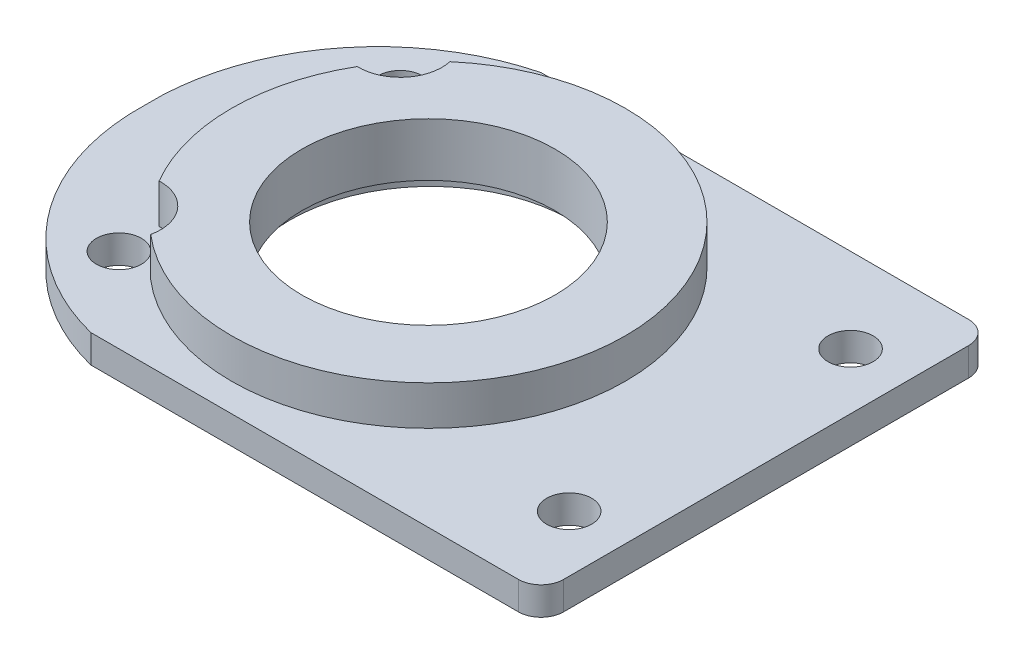
SolidWorks part; units mm, degrees
ref_plane "Front Plane" through (0, 0, 0) normal (0, 0, 1) x (1, 0, 0)
ref_plane "Top Plane" through (0, 0, 0) normal (0, 1, 0) x (1, 0, 0)
ref_plane "Right Plane" through (0, 0, 0) normal (1, 0, 0) x (0, 0, -1)
sketch "Sketch1" plane through (0, 0, 0) normal (0, 1, 0) x (1, 0, 0)
  line L1 (0, 0) -> (76.2, 0)
  line L2 (0, 0) -> (0, 50.8)
  line L3 (0, 50.8) -> (76.2, 50.8)
  line L4 (76.2, 0) -> (76.2, 50.8)
  circle A0 centre (38.1, 25.4) radius 14.2748
  dimension "D5" = 28.5496
  dimension "D1" = 50.8
  dimension "D2" = 76.2
  dimension "D3" = 38.1
  dimension "D4" = 25.4
extrude "Boss-Extrude1" add sketch "Sketch1" along normal blind 3.175
sketch "Sketch2" plane through (0, 3.175, 0) normal (0, 1, 0) x (1, 0, 0)
  circle A0 centre (38.1, 25.4) radius 22.225
  dimension "D1" = 44.45
extrude "Boss-Extrude2" add sketch "Sketch2" along normal blind 4.445
sketch "Sketch3" plane through (0, 3.175, 0) normal (0, -1, 0) x (1, 0, 0)
  circle A1 centre (38.1, -25.4) radius 14.2748
  circle A2 centre (38.1, -25.4) radius 14.2748
  dimension "D1" = 0
extrude "Cut-Extrude1" cut sketch "Sketch3" against normal through all
sketch "Sketch4" plane through (0, 0, 0) normal (0, -1, 0) x (-1, 0, 0)
  line L0 (0, 0) -> (-76.2, 0) construction
  circle A0 centre (-38.3325, 25.4) radius 15.8623
  dimension "D1" = 31.7246
  dimension "D2" = 25.4
extrude "Cut-Extrude2" cut sketch "Sketch4" against normal blind 1.6002
fillet "Fillet2" radius 2.54 4 edges at (0, 1.5875, -50.8) (76.2, 1.5875, -50.8) (0, 1.5875, 0) (76.2, 1.5875, 0)
sketch "Sketch5" plane through (0, 3.175, 0) normal (0, 1, 0) x (1, 0, 0)
  line L0 (73.66, 50.8) -> (2.54, 50.8) construction
  line L2 (2.54, 0) -> (73.66, 0) construction
  line L3 (76.2, 2.54) -> (76.2, 48.26) construction
  circle A0 centre (69.85, 41.275) radius 2.54
  circle A1 centre (69.85, 9.525) radius 2.54
  circle A2 centre (19.05, 9.525) radius 2.54
  circle A3 centre (19.05, 41.275) radius 2.54
  dimension "D9" = 5.08
  dimension "D10" = 5.08
  dimension "D11" = 5.08
  dimension "D12" = 5.08
  dimension "D1" = 9.525
  dimension "D2" = 50.8
  dimension "D3" = 50.8
  dimension "D4" = 9.525
  dimension "D5" = 9.525
  dimension "D6" = 6.35
  dimension "D7" = 9.525
  dimension "D8" = 6.35
extrude "Cut-Extrude3" cut sketch "Sketch5" against normal through all and the other way through all
sketch "Sketch6" plane through (0, 3.175, 0) normal (0, 1, 0) x (1, 0, 0)
  line L0 (2.54, 0) -> (73.66, 0) construction
  line L1 (0, 0) -> (0, 50.8)
  line L2 (73.66, 50.8) -> (2.54, 50.8) construction
  line L3 (25.4, 0) -> (0, 0)
  line L5 (25.4, 50.8) -> (0, 50.8)
  arc A0 (25.4, 0) -> (6.234, 25.3597) centre (31.6234, 24.6258) cw
  arc A1 (25.4, 50.8) -> (6.234, 25.3597) centre (31.6209, 26.1736) ccw
  line M6 (73.66, 50.8) -> (2.54, 50.8)
  arc M7 (2.54, 50.8) -> (0, 48.26) centre (2.54, 48.26) ccw
  line M8 (0, 48.26) -> (0, 2.54)
  arc M9 (0, 2.54) -> (2.54, 0) centre (2.54, 2.54) ccw
  line M10 (2.54, 0) -> (73.66, 0)
extrude "Cut-Extrude4" cut sketch "Sketch6" along direction (0, -1, 0) on the side against the normal through all contours A1 A0 M6 M7 M8 M9 M10
sketch "Sketch7" plane through (0, 3.175, 0) normal (0, 1, 0) x (1, 0, 0)
  circle A0 centre (19.05, 9.525) radius 4.699
  dimension "D1" = 9.398
extrude "Cut-Extrude5" cut sketch "Sketch7" along normal through all contours A0
sketch "Sketch9" plane through (0, 3.175, 0) normal (0, 1, 0) x (1, 0, 0)
  circle A0 centre (19.05, 41.275) radius 4.699
  dimension "D1" = 9.398
extrude "Cut-Extrude6" cut sketch "Sketch9" along normal through all contours A0
